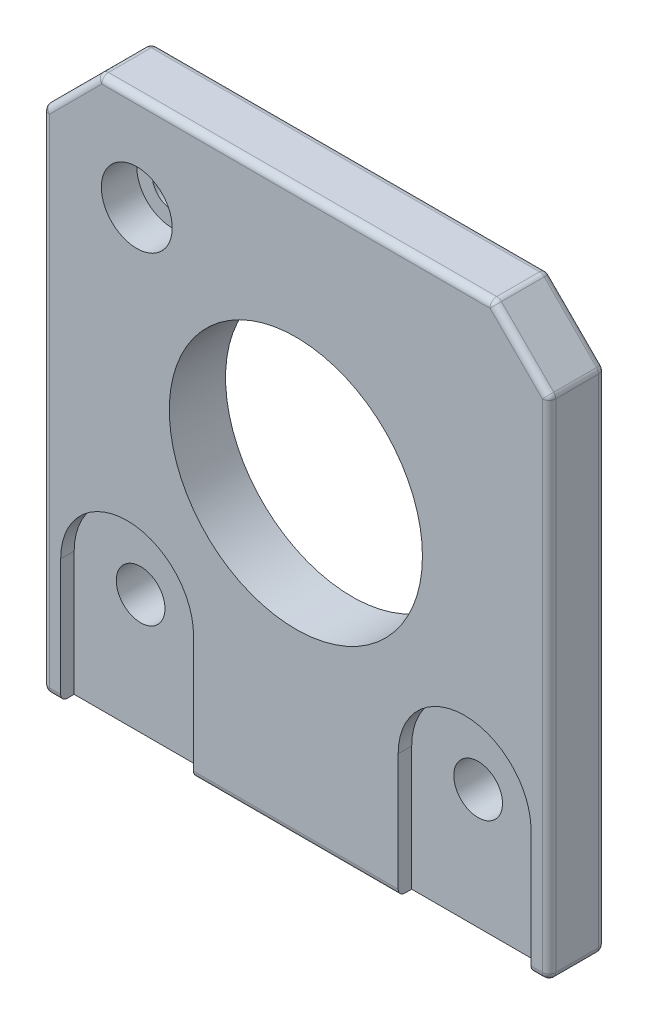
SolidWorks part; units mm, degrees
ref_plane "Front Plane" through (0, 0, 0) normal (0, 0, 1) x (1, 0, 0)
ref_plane "Top Plane" through (0, 0, 0) normal (0, 1, 0) x (1, 0, 0)
ref_plane "Right Plane" through (0, 0, 0) normal (1, 0, 0) x (0, 0, -1)
sketch "Sketch2" plane through (0, 0, 0) normal (0, 1, 0) x (1, 0, 0)
  line L1 (-28.575, 3.175) -> (28.575, 3.175)
  line L2 (-28.575, 3.175) -> (-28.575, -3.175)
  line L3 (-28.575, -3.175) -> (28.575, -3.175)
  line L4 (28.575, 3.175) -> (28.575, -3.175)
  point P4 (0, 3.175)
  point P7 (-28.575, 0)
  dimension "D1" = 6.35
  dimension "D2" = 57.15
extrude "Boss-Extrude1" add sketch "Sketch2" against normal blind 63.5
sketch "Sketch3" plane through (0, 0, 3.175) normal (0, 0, 1) x (1, 0, 0)
  line L2 (-28.575, 0) -> (28.575, 0) construction
  circle A0 centre (0, -28.815) radius 14.2875
  point P2 (0, 0)
  dimension "D1" = 28.815
  dimension "D3" = 28.575
extrude "Cut-Extrude1" cut sketch "Sketch3" against normal through all
chamfer "Chamfer1" distance 6.35 angle 45 2 edges at (-28.575, 0, 0) (28.575, 0, 0)
hole_wizard "M5 Clearance Hole1" positions "Sketch6" profile "Sketch7" hole size "M5" standard "ANSI Metric" end condition through all
sketch "Sketch6" plane through (0, 0, 3.175) normal (0, 0, 1) x (1, 0, 0)
  line L0 (-28.575, -63.5) -> (28.575, -63.5) construction
  line L1 (28.575, -63.5) -> (28.575, -6.35) construction
  point P0 (-19.05, -50)
  point P3 (19.05, -50)
  dimension "D1" = 13.5
  dimension "D2" = 9.525
  dimension "D3" = 38.1
sketch "Sketch7" plane through (-19.05, -50, 3.175) normal (1, 0, 0) x (0, -1, 0)
  line L0 (0, 0) -> (0, 6.35)
  line L1 (0, 6.35) -> (2.75, 6.35)
  line L2 (2.75, 6.35) -> (2.75, 0)
  line L5 (2.75, 0) -> (0, 0)
  line L11 (0, -6.35) -> (0, 107.95) construction
  dimension "Thru Hole Dia." = 5.5
  dimension "Thru Hole Depth" = 6.35
fillet "Fillet1" radius 0.762 18 edges at (0, -63.5, 3.175) (0, -63.5, -3.175) (28.575, -63.5, 0) (28.575, -34.925, 3.175) (28.575, -34.925, -3.175) (-28.575, -63.5, 0) (-28.575, -34.925, -3.175) (-28.575, -34.925, 3.175) (-25.4, -3.175, 3.175) (-28.575, -6.35, 0) (-25.4, -3.175, -3.175) (0, 0, 3.175) (-22.225, 0, 0) (0, 0, -3.175) (22.225, 0, 0) (25.4, -3.175, -3.175) (28.575, -6.35, 0) (25.4, -3.175, 3.175)
sketch "Sketch8" plane through (0, 0, 3.175) normal (0, 0, 1) x (1, 0, 0)
  line L0 (11.55, -63.5) -> (11.55, -49.5)
  line L1 (26.55, -49.5) -> (26.55, -63.5)
  line L2 (11.55, -63.5) -> (26.55, -63.5)
  line L3 (28.575, -63.5) -> (28.575, -6.35) construction
  line L4 (-28.575, -63.5) -> (28.575, -63.5) construction
  arc A0 (11.55, -49.5) -> (26.55, -49.5) centre (19.05, -49.5) cw
  point P3 (0, 0)
  dimension "D2" = 7.5
  dimension "D1" = 2.025
  dimension "D3" = 14
  dimension "D4" = 15
extrude "Cut-Extrude4" cut sketch "Sketch8" against normal blind 1.524
mirror "Mirror1" about plane through (0, 0, 0) normal (1, 0, 0) of "Cut-Extrude4"
hole_wizard "CBORE for M4 SHCS2" positions "Sketch9" profile "Sketch10" counterbore size "M4" standard "ANSI Metric" end condition through all
sketch "Sketch9" plane through (0, 0, 3.175) normal (0, 0, 1) x (1, 0, 0)
  line L0 (-21.9094, 0) -> (21.9094, 0) construction
  point P0 (-17.9605, -10.8545)
  dimension "D1" = 10.8545
  dimension "D2" = 17.9605
sketch "Sketch10" plane through (-17.9605, -10.8545, 3.175) normal (1, 0, 0) x (0, -1, 0)
  line L0 (0, 0) -> (0, 6.35)
  line L1 (0, 6.35) -> (2.25, 6.35)
  line L3 (2.25, 6.35) -> (2.25, 4)
  line L4 (2.25, 4) -> (4, 4)
  line L5 (4, 4) -> (4, 0)
  line L7 (4, 0) -> (0, 0)
  line L11 (0, -6.35) -> (0, 107.95) construction
  dimension "Thru Hole Dia." = 4.5
  dimension "Thru Hole Depth" = 6.35
  dimension "C'Bore Dia." = 8
  dimension "C'Bore Depth" = 4
